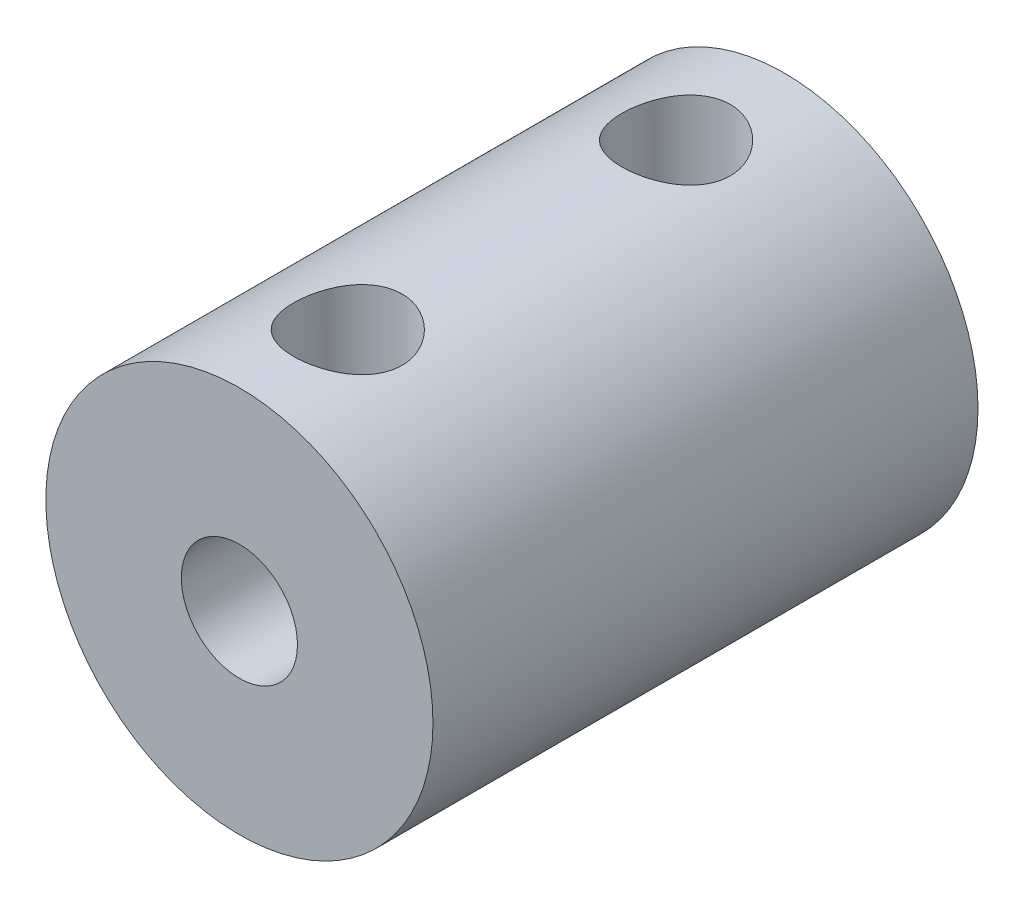
SolidWorks part; units mm, degrees
ref_plane "Front Plane" through (0, 0, 0) normal (0, 0, 1) x (1, 0, 0)
ref_plane "Top Plane" through (0, 0, 0) normal (0, 1, 0) x (1, 0, 0)
ref_plane "Right Plane" through (0, 0, 0) normal (1, 0, 0) x (0, 0, -1)
sketch "Sketch1" plane through (0, 0, 0) normal (0, 0, 1) x (1, 0, 0)
  circle A0 centre (0, 0) radius 7.9375
  dimension "D1" = 15.875
extrude "Boss-Extrude1" add sketch "Sketch1" along normal blind 22.352
sketch "Sketch2" plane through (0, 0, 22.352) normal (0, 0, 1) x (1, 0, 0)
  circle A0 centre (0, 0) radius 2.3813
  dimension "D1" = 4.7625
extrude "Cut-Extrude1" cut sketch "Sketch2" against normal through all
sketch "Sketch3" plane through (0, 0, 0) normal (0, 1, 0) x (1, 0, 0)
  line L0 (0, 0) -> (0, -22.352) construction
  line L1 (-7.9375, -22.352) -> (7.9375, -22.352) construction
  line L2 (7.9375, 0) -> (-7.9375, 0) construction
  circle A0 centre (0, -4.445) radius 2.2225
  circle A1 centre (0, -17.907) radius 2.2225
  dimension "D1" = 4.445
  dimension "D2" = 4.445
  dimension "D3" = 4.445
extrude "Cut-Extrude2" cut sketch "Sketch3" along normal through all
